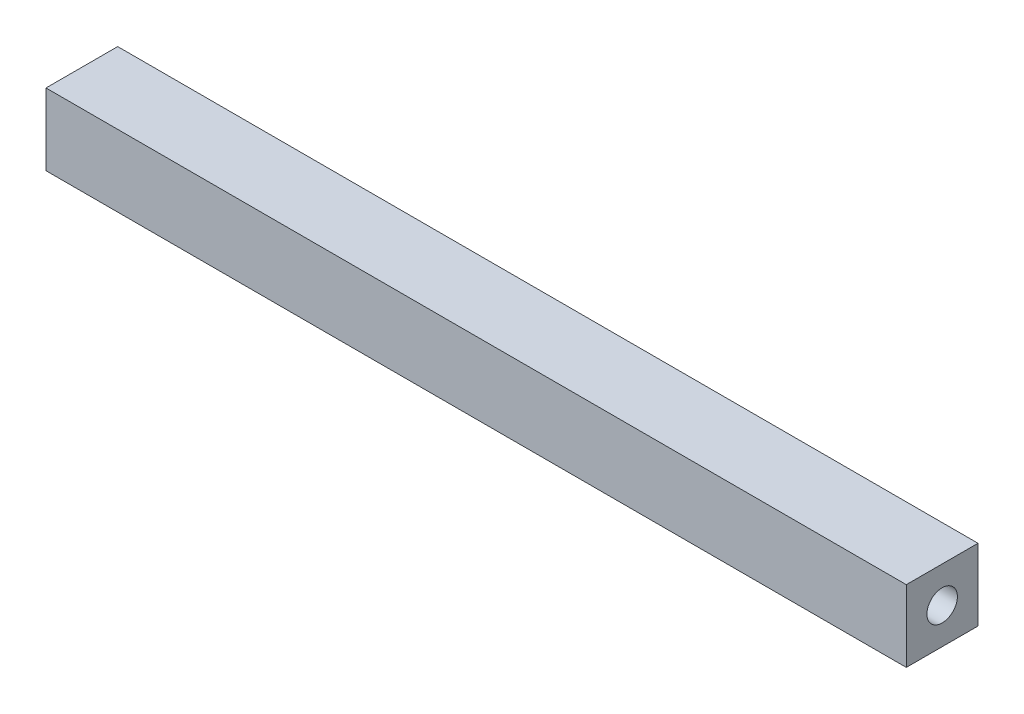
SolidWorks part; units mm, degrees
ref_plane "Plano frontal" through (0, 0, 0) normal (0, 0, 1) x (1, 0, 0)
ref_plane "Plano superior" through (0, 0, 0) normal (0, 1, 0) x (1, 0, 0)
ref_plane "Plano direito" through (0, 0, 0) normal (1, 0, 0) x (0, 0, -1)
sketch "Esboço1" plane through (0, 0, 0) normal (1, 0, 0) x (0, 0, -1)
  line L1 (2, -2) -> (-2, -2)
  line L2 (2, -2) -> (2, 2)
  line L3 (2, 2) -> (-2, 2)
  line L4 (-2, -2) -> (-2, 2)
  line L5 (2, -2) -> (-2, 2) construction
  line L6 (2, 2) -> (-2, -2) construction
  point P0 (0, 0)
  dimension "D1" = 4
extrude "Ressalto-extrusão1" add sketch "Esboço1" along normal mid plane 48
sketch "Esboço2" plane through (24, 0, 0) normal (1, 0, 0) x (0, 0, -1)
  circle A0 centre (0, 0) radius 0.85
  dimension "D1" = 1.7
extrude "Corte-extrusão1" cut sketch "Esboço2" against normal through all and the other way through all
